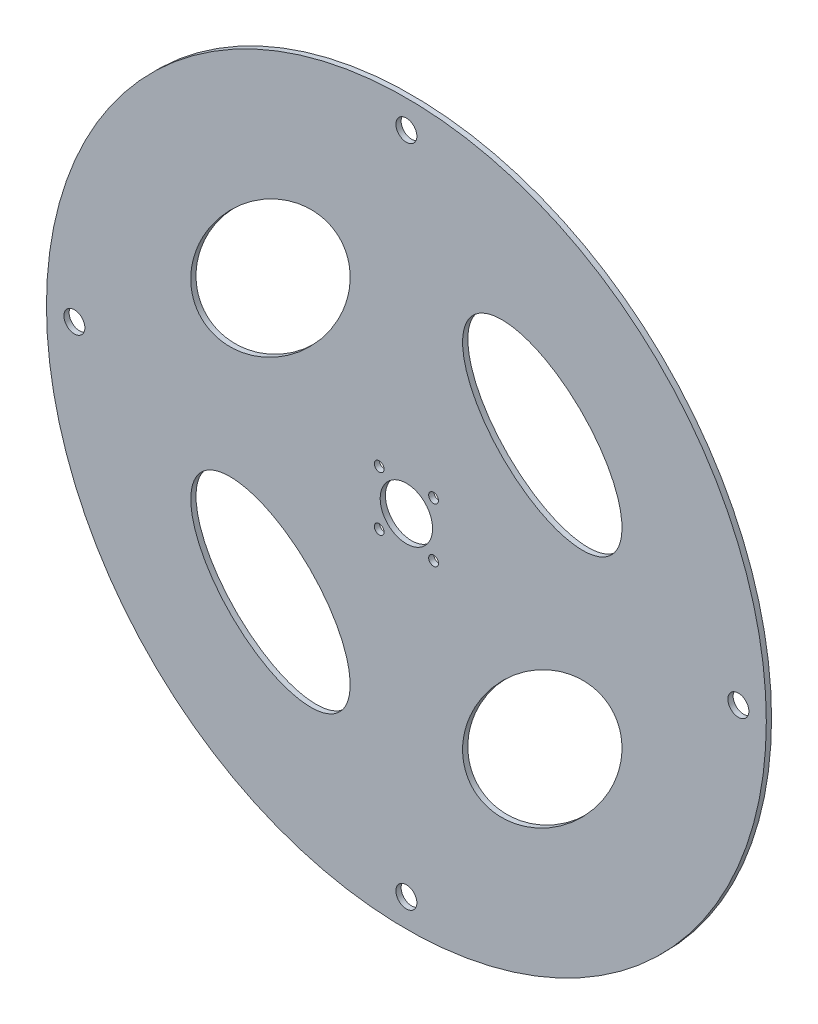
SolidWorks part; units mm, degrees
ref_plane "Front Plane" through (0, 0, 0) normal (0, 0, 1) x (1, 0, 0)
ref_plane "Top Plane" through (0, 0, 0) normal (0, 1, 0) x (1, 0, 0)
ref_plane "Right Plane" through (0, 0, 0) normal (1, 0, 0) x (0, 0, -1)
sketch "Sketch1" plane through (0, 0, 0) normal (0, 0, 1) x (1, 0, 0)
  circle A0 centre (0, 0) radius 103
  dimension "D1" = 206
extrude "Base Disc" add sketch "Sketch1" along normal blind 1.5
sketch "Sketch2" plane through (0, 0, 0) normal (0, 0, -1) x (-1, 0, 0)
  circle A0 centre (0, 0) radius 7.5
  point P4 (0, 0)
sketch "Sketch3" plane through (0, 0, 0) normal (0, 0, -1) x (-1, 0, 0)
  circle A0 centre (95, 0) radius 3
  dimension "D1" = 6
  dimension "D2" = 95
extrude "Cut-Extrude1" cut sketch "Sketch3" against normal through all
sketch "Sketch4" plane through (0, 0, 0) normal (0, 0, -1) x (-1, 0, 0)
  line L0 (0, 0) -> (38.8909, 38.8909) construction
  ellipse E0 centre (38.8909, 38.8909) end of major axis (19.0919, 58.6899) minor radius 16
extrude "Cut-Extrude2" cut sketch "Sketch4" against normal through all
extrude "Cut-Extrude3" cut sketch "Sketch2" against normal through all
pattern_circular "CirPattern3" count 4 over 360 about axis through (0, 0, 0) along (0, 0, 1) of "Cut-Extrude1"
pattern_circular "CirPattern4" count 4 over 360 about axis through (0, 0, 0) along (0, 0, -1) of "Cut-Extrude2"
sketch "Sketch5" plane through (0, 0, 0) normal (0, 0, 1) x (1, 0, 0)
  line L0 (-15.8162, -15.8162) -> (-7.7782, -7.7782) construction
  line L1 (707.1068, -707.1068) -> (-6.7882, 6.7882) construction
  line L2 (-7.7782, 7.7782) -> (-720.1946, 720.1946) construction
  line L3 (-6.7882, -6.7882) -> (7.5537, 7.5537) construction
  circle A1 centre (-7.7782, -7.7782) radius 1.4
  circle A2 centre (-7.7782, 7.7782) radius 1.4
  circle A3 centre (7.7782, 7.7782) radius 1.4
  circle A4 centre (7.7782, -7.7782) radius 1.4
  point P18 (0, 0)
  dimension "D1" = 4
extrude "Cut-Extrude4" cut sketch "Sketch5" along normal through all
